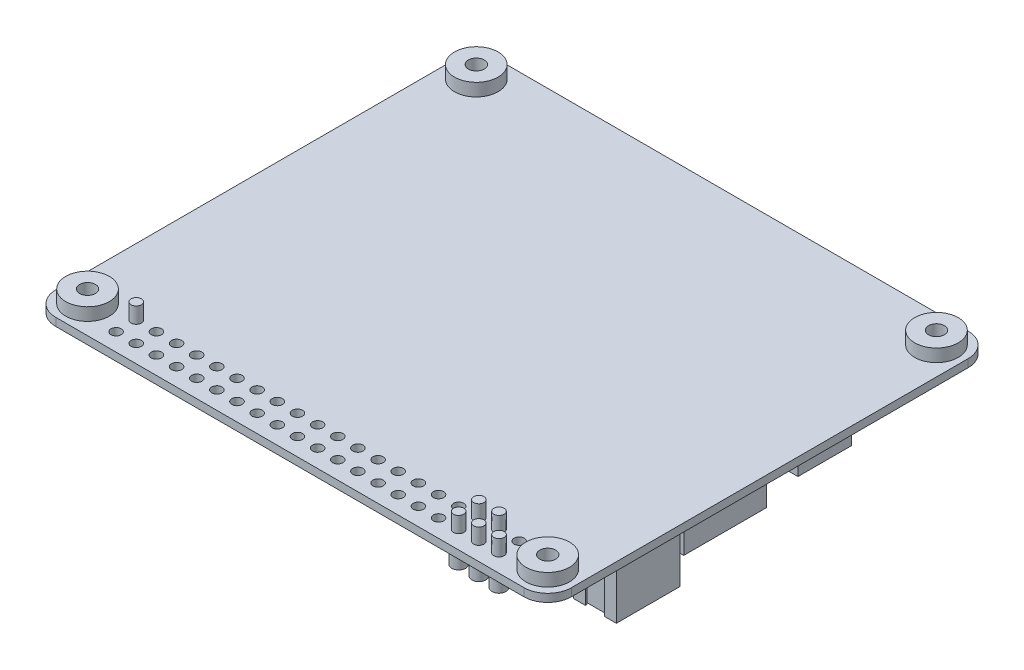
SolidWorks part; units mm, degrees
ref_plane "前视基准面" through (0, 0, 0) normal (0, 0, 1) x (1, 0, 0)
ref_plane "上视基准面" through (0, 0, 0) normal (0, 1, 0) x (1, 0, 0)
ref_plane "右视基准面" through (0, 0, 0) normal (1, 0, 0) x (0, 0, -1)
sketch "草图1" plane through (0, 0, 0) normal (0, 1, 0) x (1, 0, 0)
  line L1 (32.5, -28) -> (-32.5, -28)
  line L2 (32.5, -28) -> (32.5, 28)
  line L3 (32.5, 28) -> (-32.5, 28)
  line L4 (-32.5, -28) -> (-32.5, 28)
  line L5 (32.5, -28) -> (-32.5, 28) construction
  line L6 (32.5, 28) -> (-32.5, -28) construction
  point P0 (0, 0)
  dimension "D1" = 56
  dimension "D2" = 65
extrude "凸台-拉伸1" add sketch "草图1" along normal blind 1
fillet "圆角1" radius 3 4 edges at (32.5, 0.5, -28) (32.5, 0.5, 28) (-32.5, 0.5, 28) (-32.5, 0.5, -28)
sketch "草图2" plane through (0, 1, 0) normal (0, 1, 0) x (1, 0, 0)
  line L0 (-29, -24.5) -> (-29, 24.5) construction
  line L1 (-32.5, 0) -> (-29, 0) construction
  line L2 (-32.5, 25) -> (-32.5, -25) construction
  line L3 (29, 24.5) -> (29, -24.5) construction
  line L4 (29, 0) -> (32.5, 0) construction
  line L5 (32.5, -25) -> (32.5, 25) construction
  circle A0 centre (-29, 24.5) radius 2.75
  circle A1 centre (29, 24.5) radius 2.75
  circle A2 centre (-29, -24.5) radius 2.75
  circle A3 centre (29, -24.5) radius 2.75
  point P16 (28.9437, 21.4052)
  dimension "D1" = 5.5
  dimension "D2" = 49
  dimension "D3" = 58
extrude "凸台-拉伸2" add sketch "草图2" along normal blind 1.6
sketch "草图3" plane through (0, 2.6, 0) normal (0, 1, 0) x (1, 0, 0)
  circle A0 centre (-29, 24.5) radius 1
  circle A1 centre (29, 24.5) radius 1
  circle A2 centre (-29, -24.5) radius 1
  circle A3 centre (29, -24.5) radius 1
  dimension "D1" = 2
extrude "切除-拉伸1" cut sketch "草图3" against normal up to next
sketch "草图4" plane through (0, 0, 0) normal (0, -1, 0) x (1, 0, 0)
  line L0 (29.5, -28) -> (-29.5, -28) construction
  line L1 (25.5, -28) -> (16.5, -28)
  line L2 (25.5, -28) -> (25.5, -20.6)
  line L3 (25.5, -20.6) -> (16.5, -20.6)
  line L4 (16.5, -28) -> (16.5, -20.6)
  line L5 (32.5, 25) -> (32.5, -25) construction
  dimension "D1" = 7.4
  dimension "D2" = 9
  dimension "D3" = 7
extrude "凸台-拉伸3" add sketch "草图4" along normal blind 3.2
sketch "草图5" plane through (0, 0, -28) normal (0, 0, -1) x (-1, 0, 0)
  line L0 (-29.5, 0) -> (-25.5, 0) construction
  line L1 (-16.5, -3.2) -> (-25.5, -3.2)
  line L2 (-16.5, -3.2) -> (-16.5, 0)
  line L3 (-16.5, 0) -> (-25.5, 0)
  line L4 (-25.5, -3.2) -> (-25.5, 0)
  line L5 (-25.5, -3.2) -> (-25.5, 0) construction
extrude "凸台-拉伸4" add sketch "草图5" along normal blind 1
fillet "圆角3" radius 1 4 edges at (25.5, 0, -28.5) (25.5, -3.2, -24.8) (16.5, -3.2, -24.8) (16.5, 0, -28.5)
sketch "草图6" plane through (0, 0, 0) normal (0, -1, 0) x (1, 0, 0)
  line L0 (-32.5, -25) -> (-32.5, 25) construction
  circle A0 centre (-17.5, 0) radius 7
  point P4 (0, 0)
  dimension "D1" = 14
  dimension "D2" = 15
extrude "凸台-拉伸5" add sketch "草图6" along normal blind 2
sketch "草图8" plane through (0, 0, 0) normal (0, -1, 0) x (1, 0, 0)
  circle A0 centre (29, 24.5) radius 2
  circle A1 centre (29, -24.5) radius 2
  circle A2 centre (-29, -24.5) radius 2
  circle A3 centre (-29, 24.5) radius 2
  point P8 (29, -24.5)
  point P10 (29, 24.5)
  point P12 (-29, 24.5)
  point P14 (-29, -24.5)
  dimension "D1" = 4
extrude "凸台-拉伸6" add sketch "草图8" along normal blind 0.5
sketch "草图9" plane through (0, 0, 0) normal (0, 1, 0) x (1, 0, 0)
  circle A0 centre (-29, 24.5) radius 1
  circle A1 centre (29, 24.5) radius 1
  circle A2 centre (-29, -24.5) radius 1
  circle A3 centre (29, -24.5) radius 1
  circle A4 centre (29, -24.5) radius 2 construction
  circle A5 centre (29, 24.5) radius 2 construction
  circle A6 centre (-29, -24.5) radius 2 construction
  circle A7 centre (-29, 24.5) radius 2 construction
  point P16 (-29, -24.5)
  dimension "D1" = 2
extrude "切除-拉伸2" cut sketch "草图9" against normal up to next
sketch "草图10" plane through (0, 0, -29) normal (0, 0, -1) x (-1, 0, 0)
  line L8 (-17.5, -0.2) -> (-24.5, -0.2)
  line L9 (-25.3, -1) -> (-25.3, -2.2)
  line L10 (-24.5, -3) -> (-17.5, -3)
  line L11 (-16.7, -2.2) -> (-16.7, -1)
  line L12 (-17.5, -0.2) -> (-24.5, -0.2)
  line L13 (-25.3, -1) -> (-25.3, -2.2)
  line L14 (-24.5, -3) -> (-17.5, -3)
  line L15 (-16.7, -2.2) -> (-16.7, -1)
  arc A8 (-24.5, -0.2) -> (-25.3, -1) centre (-24.5, -1) ccw
  arc A9 (-25.3, -2.2) -> (-24.5, -3) centre (-24.5, -2.2) ccw
  arc A10 (-17.5, -3) -> (-16.7, -2.2) centre (-17.5, -2.2) ccw
  arc A11 (-16.7, -1) -> (-17.5, -0.2) centre (-17.5, -1) ccw
  arc A12 (-24.5, -0.2) -> (-25.3, -1) centre (-24.5, -1) ccw
  arc A13 (-25.3, -2.2) -> (-24.5, -3) centre (-24.5, -2.2) ccw
  arc A14 (-17.5, -3) -> (-16.7, -2.2) centre (-17.5, -2.2) ccw
  arc A15 (-16.7, -1) -> (-17.5, -0.2) centre (-17.5, -1) ccw
  dimension "D1" = 0.2
extrude "切除-拉伸3" cut sketch "草图10" against normal blind 8
sketch "草图12" plane through (0, 0, 0) normal (0, -1, 0) x (1, 0, 0)
  line L0 (16.5, -28) -> (-29.5, -28) construction
  line L1 (-16.6, -28) -> (-23.9, -28)
  line L2 (-16.6, -28) -> (-16.6, -22.7)
  line L3 (-16.6, -22.7) -> (-23.9, -22.7)
  line L4 (-23.9, -28) -> (-23.9, -22.7)
  line L5 (-32.5, -25) -> (-32.5, 25) construction
  dimension "D1" = 7.3
  dimension "D2" = 8.6
  dimension "D3" = 5.3
extrude "凸台-拉伸8" add sketch "草图12" along normal blind 2.4
sketch "草图13" plane through (0, 0, -28) normal (0, 0, -1) x (-1, 0, 0)
  line L1 (23.9, -2.4) -> (16.6, -2.4)
  line L2 (23.9, -2.4) -> (23.9, 0)
  line L3 (23.9, 0) -> (16.6, 0)
  line L4 (16.6, -2.4) -> (16.6, 0)
extrude "凸台-拉伸9" add sketch "草图13" along normal up to surface (1 mm away) up to face at (21, -1.6, -29)
chamfer "倒角1" distance 0.4 angle 45 2 edges at (-16.6, -2.4, -25.85) (-23.9, -2.4, -25.85)
chamfer "倒角2" distance 1 angle 45 2 edges at (-16.6, 0, -28.5) (-23.9, 0, -28.5)
sketch "草图14" plane through (0, 0, -29) normal (0, 0, -1) x (-1, 0, 0)
  line L16 (22.8172, -0.2) -> (17.6828, -0.2)
  line L17 (17.6828, -0.2) -> (16.8, -1.0828)
  line L18 (16.8, -1.0828) -> (16.8, -1.9172)
  line L19 (16.8, -1.9172) -> (17.0828, -2.2)
  line L20 (17.0828, -2.2) -> (23.4172, -2.2)
  line L21 (23.4172, -2.2) -> (23.7, -1.9172)
  line L22 (23.7, -1.9172) -> (23.7, -1.0828)
  line L23 (23.7, -1.0828) -> (22.8172, -0.2)
  line L24 (22.8172, -0.2) -> (17.6828, -0.2)
  line L25 (17.6828, -0.2) -> (16.8, -1.0828)
  line L26 (16.8, -1.0828) -> (16.8, -1.9172)
  line L27 (16.8, -1.9172) -> (17.0828, -2.2)
  line L28 (17.0828, -2.2) -> (23.4172, -2.2)
  line L29 (23.4172, -2.2) -> (23.7, -1.9172)
  line L30 (23.7, -1.9172) -> (23.7, -1.0828)
  line L31 (23.7, -1.0828) -> (22.8172, -0.2)
  dimension "D1" = 0.2
extrude "切除-拉伸4" cut sketch "草图14" against normal blind 2.4
sketch "草图17" plane through (0, 0, -28) normal (0, 0, -1) x (-1, 0, 0)
  line L0 (23.9, -1) -> (23.9, 0)
  line L1 (23.9, 0) -> (22.9, 0)
  line L2 (22.9, 0) -> (23.9, -1)
  line L3 (16.6, 0) -> (17.6, 0)
  line L4 (17.6, 0) -> (16.6, -1)
  line L5 (16.6, -1) -> (16.6, 0) construction
  line L6 (16.6, -1) -> (16.6, 0)
extrude "切除-拉伸5" cut sketch "草图17" against normal up to surface (5.3 mm away) up to face at (-20.25, -1.4667, -22.7)
fillet "圆角4" radius 0.2 1 edges at (-17.5, -2, -7)
sketch "草图19" plane through (0, 0, 0) normal (0, -1, 0) x (1, 0, 0)
  line L0 (32.5, 25) -> (32.5, -25) construction
  line L1 (32, 18.85) -> (26.6, 18.85)
  line L2 (32, 18.85) -> (32, 10.85)
  line L3 (32, 10.85) -> (26.6, 10.85)
  line L4 (26.6, 18.85) -> (26.6, 10.85)
  line L5 (-29.5, 28) -> (29.5, 28) construction
  dimension "D1" = 8
  dimension "D2" = 5.4
  dimension "D3" = 0.5
  dimension "D4" = 9.15
extrude "凸台-拉伸13" add sketch "草图19" along normal blind 6.22
sketch "草图20" plane through (0, -6.22, 0) normal (0, -1, 0) x (1, 0, 0)
  line L0 (30.5, 18.85) -> (30.5, 18.65)
  line L1 (32, 18.85) -> (26.6, 18.85) construction
  line L2 (30.5, 18.65) -> (31.3599, 18.65)
  line L3 (31.3599, 18.65) -> (31.3599, 18.45)
  line L4 (31.3599, 18.45) -> (26.9378, 18.45)
  line L5 (26.9378, 18.45) -> (26.9378, 18.65)
  line L6 (26.9378, 18.65) -> (28.1, 18.65)
  line L7 (28.1, 18.65) -> (28.1, 18.85)
  line L8 (32, 18.85) -> (26.6, 18.85) construction
  line L9 (28.1, 18.85) -> (30.5, 18.85)
  line L10 (30.5, 10.85) -> (30.5, 11.05)
  line L11 (26.6, 10.85) -> (32, 10.85) construction
  line L12 (30.5, 11.05) -> (31.3599, 11.05)
  line L13 (31.3599, 11.05) -> (31.3599, 11.25)
  line L14 (31.3599, 11.25) -> (26.9378, 11.25)
  line L15 (26.9378, 11.25) -> (26.9378, 11.05)
  line L16 (26.9378, 11.05) -> (28.1, 11.05)
  line L17 (28.1, 11.05) -> (28.1, 10.85)
  line L18 (28.1, 10.85) -> (30.5, 10.85)
  line L19 (32, 10.85) -> (32, 18.85) construction
  line L20 (26.6, 18.85) -> (26.6, 10.85) construction
  dimension "D1" = 0.2
  dimension "D2" = 0.2
  dimension "D3" = 0.2
  dimension "D4" = 1.5
  dimension "D5" = 1.5
  dimension "D6" = 4.4222
  dimension "D7" = 0.6401
extrude "切除-拉伸6" cut sketch "草图20" against normal blind 6.22
sketch "草图21" plane through (0, -6.22, 0) normal (0, -1, 0) x (1, 0, 0)
  line L1 (31.3599, 18.0753) -> (26.9378, 18.0753)
  line L2 (31.3599, 18.0753) -> (31.3599, 11.6247)
  line L3 (31.3599, 11.6247) -> (26.9378, 11.6247)
  line L4 (26.9378, 18.0753) -> (26.9378, 11.6247)
  line L5 (31.3599, 18.0753) -> (26.9378, 11.6247) construction
  line L6 (31.3599, 11.6247) -> (26.9378, 18.0753) construction
  point P0 (29.1489, 14.85)
extrude "切除-拉伸7" cut sketch "草图21" against normal blind 5
sketch "草图22" plane through (0, -1.22, 0) normal (0, -1, 0) x (1, 0, 0)
  line L1 (29.5742, 16.0721) -> (29.0742, 16.0721)
  line L2 (29.5742, 16.0721) -> (29.5742, 15.5721)
  line L3 (29.5742, 15.5721) -> (29.0742, 15.5721)
  line L4 (29.0742, 16.0721) -> (29.0742, 15.5721)
  line L5 (29.5742, 16.0721) -> (29.0742, 15.5721) construction
  line L6 (29.5742, 15.5721) -> (29.0742, 16.0721) construction
  line L7 (29.5566, 14.331) -> (29.0566, 14.331)
  line L8 (29.5566, 14.331) -> (29.5566, 13.831)
  line L9 (29.5566, 13.831) -> (29.0566, 13.831)
  line L10 (29.0566, 14.331) -> (29.0566, 13.831)
  line L11 (29.5566, 14.331) -> (29.0566, 13.831) construction
  line L12 (29.5566, 13.831) -> (29.0566, 14.331) construction
  point P0 (29.3242, 15.8221)
  point P5 (29.3066, 14.081)
  dimension "D1" = 0.5
extrude "凸台-拉伸14" add sketch "草图22" along normal blind 5
chamfer "倒角3" distance 0.1 angle 45 8 edges at (29.3066, -6.22, 14.331) (29.5566, -6.22, 14.081) (29.3066, -6.22, 13.831) (29.0566, -6.22, 14.081) (29.3242, -6.22, 16.0721) (29.5742, -6.22, 15.8221) (29.3242, -6.22, 15.5721) (29.0742, -6.22, 15.8221)
sketch "草图26" plane through (0, 0, 0) normal (0, -1, 0) x (1, 0, 0)
  line L0 (-29.5, 28) -> (29.5, 28) construction
  line L1 (-24.13, 25.77) -> (24.13, 25.77) construction
  line L2 (32.5, 25) -> (32.5, -25) construction
  line L3 (24.13, 23.23) -> (-24.13, 23.23) construction
  circle A0 centre (24.13, 25.77) radius 0.65
  circle A40 centre (21.59, 25.77) radius 0.65
  circle A41 centre (19.05, 25.77) radius 0.65
  circle A42 centre (16.51, 25.77) radius 0.65
  circle A43 centre (13.97, 25.77) radius 0.65
  circle A44 centre (11.43, 25.77) radius 0.65
  circle A45 centre (8.89, 25.77) radius 0.65
  circle A46 centre (6.35, 25.77) radius 0.65
  circle A47 centre (3.81, 25.77) radius 0.65
  circle A48 centre (1.27, 25.77) radius 0.65
  circle A49 centre (-1.27, 25.77) radius 0.65
  circle A50 centre (-3.81, 25.77) radius 0.65
  circle A51 centre (-6.35, 25.77) radius 0.65
  circle A52 centre (-8.89, 25.77) radius 0.65
  circle A53 centre (-11.43, 25.77) radius 0.65
  circle A54 centre (-13.97, 25.77) radius 0.65
  circle A55 centre (-16.51, 25.77) radius 0.65
  circle A56 centre (-19.05, 25.77) radius 0.65
  circle A57 centre (-21.59, 25.77) radius 0.65
  circle A58 centre (-24.13, 25.77) radius 0.65
  circle A59 centre (21.59, 23.23) radius 0.65
  circle A60 centre (19.05, 23.23) radius 0.65
  circle A61 centre (16.51, 23.23) radius 0.65
  circle A62 centre (13.97, 23.23) radius 0.65
  circle A63 centre (11.43, 23.23) radius 0.65
  circle A64 centre (8.89, 23.23) radius 0.65
  circle A65 centre (6.35, 23.23) radius 0.65
  circle A66 centre (3.81, 23.23) radius 0.65
  circle A67 centre (1.27, 23.23) radius 0.65
  circle A68 centre (-1.27, 23.23) radius 0.65
  circle A69 centre (-3.81, 23.23) radius 0.65
  circle A70 centre (-6.35, 23.23) radius 0.65
  circle A71 centre (-8.89, 23.23) radius 0.65
  circle A72 centre (-11.43, 23.23) radius 0.65
  circle A73 centre (-13.97, 23.23) radius 0.65
  circle A74 centre (-16.51, 23.23) radius 0.65
  circle A75 centre (-19.05, 23.23) radius 0.65
  circle A76 centre (-21.59, 23.23) radius 0.65
  circle A77 centre (-24.13, 23.23) radius 0.65
  circle A78 centre (24.13, 23.23) radius 0.65
  point P82 (0, 0)
  dimension "D1" = 1.3
  dimension "D4" = 2.23
  dimension "D5" = 48.26
  dimension "D6" = 8.37
  dimension "D7" = 2.54
  dimension "D2" = 20
  dimension "D3" = 2
extrude "切除-拉伸8" cut sketch "草图26" against normal up to surface (1 mm away) up to face at (29, 1, 27.25)
sketch "草图27" plane through (0, 0, 0) normal (0, -1, 0) x (1, 0, 0)
  circle A0 centre (24.13, 25.77) radius 1.15
  circle A1 centre (21.59, 25.77) radius 1.15
  circle A2 centre (21.59, 23.23) radius 1.15
  circle A3 centre (19.05, 25.77) radius 1.15
  circle A4 centre (19.05, 23.23) radius 1.15
  circle A5 centre (13.97, 23.23) radius 1.15
  circle A6 centre (21.59, 25.77) radius 0.65 construction
  dimension "D1" = 2.3
extrude "凸台-拉伸18" add sketch "草图27" along normal blind 0.8
sketch "草图28" plane through (0, -0.8, 0) normal (0, -1, 0) x (-1, 0, 0)
  circle A0 centre (-24.13, -25.77) radius 0.875
  circle A1 centre (-21.59, -25.77) radius 0.875
  circle A2 centre (-19.05, -23.23) radius 0.875
  circle A3 centre (-21.59, -23.23) radius 0.875
  circle A4 centre (-19.05, -25.77) radius 0.875
  circle A5 centre (-13.97, -23.23) radius 0.875
  dimension "D1" = 1.75
extrude "凸台-拉伸19" add sketch "草图28" along normal blind 2
sketch "草图29" plane through (0, 0, 0) normal (0, 1, 0) x (1, 0, 0)
  circle A0 centre (19.05, -23.23) radius 0.65 construction
  circle A1 centre (19.05, -25.77) radius 0.65 construction
  circle A2 centre (21.59, -23.23) radius 0.65 construction
  circle A4 centre (24.13, -25.77) radius 0.65 construction
  circle A5 centre (-24.13, -23.23) radius 0.65 construction
  circle A6 centre (19.05, -23.23) radius 0.65
  circle A7 centre (19.05, -25.77) radius 0.65
  circle A8 centre (21.59, -23.23) radius 0.65
  circle A9 centre (21.59, -25.77) radius 0.65
  circle A10 centre (24.13, -25.77) radius 0.65
  circle A11 centre (-24.13, -23.23) radius 0.65
  circle A12 centre (21.59, -25.77) radius 0.65 construction
extrude "凸台-拉伸20" add sketch "草图29" along normal blind 3
sketch "草图30" plane through (0, 0, -28) normal (0, 0, -1) x (-1, 0, 0)
  line L0 (-16.5, 0) -> (-17.5, 0)
  line L1 (-16.5, 0) -> (-16.5, -1) construction
  line L2 (-16.5, 0) -> (-16.5, -1)
  line L3 (-25.5, 0) -> (-24.5, 0)
  line L4 (-25.5, -1) -> (-25.5, 0) construction
  line L5 (-25.5, -1) -> (-25.5, 0)
  arc A0 (-16.5, -1) -> (-17.5, 0) centre (-17.5, -1) ccw construction
  arc A1 (-16.5, -1) -> (-17.5, 0) centre (-17.5, -1) ccw
  arc A2 (-24.5, 0) -> (-25.5, -1) centre (-24.5, -1) ccw construction
  arc A3 (-24.5, 0) -> (-25.5, -1) centre (-24.5, -1) ccw
extrude "切除-拉伸9" cut sketch "草图30" against normal up to next
sketch "草图31" plane through (0, 0, 0) normal (0, -1, 0) x (1, 0, 0)
  line L0 (-269.1222, 141.019) -> (182.8778, 141.019) construction
  line L1 (24.5, -20.6) -> (17.5, -20.6) construction
  line L2 (31.459, 9.8102) -> (19.8345, 9.8102)
  line L3 (31.459, 9.8102) -> (31.459, -0.6109)
  line L4 (31.459, -0.6109) -> (19.8345, -0.6109)
  line L5 (19.8345, 9.8102) -> (19.8345, -0.6109)
  line L6 (31.459, -1.1785) -> (28.1669, -1.1785)
  line L7 (31.459, -1.1785) -> (31.459, -4.516)
  line L8 (31.459, -4.516) -> (28.1669, -4.516)
  line L9 (28.1669, -1.1785) -> (28.1669, -4.516)
  line L10 (27.1452, -1.4056) -> (22.332, -1.4056)
  line L11 (27.1452, -1.4056) -> (27.1452, -4.1981)
  line L12 (27.1452, -4.1981) -> (22.332, -4.1981)
  line L13 (22.332, -1.4056) -> (22.332, -4.1981)
  line L14 (31.0503, -4.9928) -> (23.558, -4.9928)
  line L15 (31.0503, -4.9928) -> (31.0503, -11.7586)
  line L16 (31.0503, -11.7586) -> (23.558, -11.7586)
  line L17 (23.558, -4.9928) -> (23.558, -11.7586)
  line L18 (31.459, -13.2884) -> (30.0812, -13.2884)
  line L19 (31.459, -13.2884) -> (31.459, -15.1195)
  line L20 (31.459, -15.1195) -> (30.0812, -15.1195)
  line L21 (30.0812, -13.2884) -> (30.0812, -15.1195)
  line L22 (29.3946, -12.2203) -> (27.6398, -12.2203)
  line L23 (29.3946, -12.2203) -> (29.3946, -13.0596)
  line L24 (29.3946, -13.0596) -> (27.6398, -13.0596)
  line L25 (27.6398, -12.2203) -> (27.6398, -13.0596)
  line L26 (25.1221, -19.2775) -> (23.024, -19.2775)
  line L27 (25.1221, -19.2775) -> (25.1221, -20.6)
  line L28 (25.1221, -20.6) -> (23.024, -20.6)
  line L29 (23.024, -19.2775) -> (23.024, -20.6)
  line L30 (24.5, -20.6) -> (17.5, -20.6) construction
  line L31 (21.8033, -19.2775) -> (20.7352, -19.2775)
  line L32 (21.8033, -19.2775) -> (21.8033, -20.6)
  line L33 (21.8033, -20.6) -> (20.7352, -20.6)
  line L34 (20.7352, -19.2775) -> (20.7352, -20.6)
  line L35 (-4.9095, -24.5987) -> (-6.2095, -24.5987)
  line L36 (20.2393, -19.2775) -> (19.2474, -19.2775)
  line L37 (20.2393, -19.2775) -> (20.2393, -20.6)
  line L38 (20.2393, -20.6) -> (19.2474, -20.6)
  line L39 (19.2474, -19.2775) -> (19.2474, -20.6)
  line L40 (25.1221, -17.065) -> (23.024, -17.065)
  line L41 (25.1221, -17.065) -> (25.1221, -18.5146)
  line L42 (25.1221, -18.5146) -> (23.024, -18.5146)
  line L43 (23.024, -17.065) -> (23.024, -18.5146)
  line L44 (21.2692, -13.0596) -> (18.103, -13.0596)
  line L45 (21.2692, -13.0596) -> (21.2692, -16.3402)
  line L46 (21.2692, -16.3402) -> (18.103, -16.3402)
  line L47 (18.103, -13.0596) -> (18.103, -16.3402)
  line L48 (19.2474, -0.6109) -> (18.4047, -0.6109)
  line L49 (19.2474, -0.6109) -> (19.2474, -2.216)
  line L50 (19.2474, -2.216) -> (18.4047, -2.216)
  line L51 (18.4047, -0.6109) -> (18.4047, -2.216)
  line L52 (13.1588, -24.973) -> (8.3931, -24.973)
  line L53 (13.1588, -24.973) -> (13.1588, -27.3005)
  line L54 (13.1588, -27.3005) -> (8.3931, -27.3005)
  line L55 (8.3931, -24.973) -> (8.3931, -27.3005)
  line L56 (4.6988, -24.973) -> (0, -24.973)
  line L57 (4.6988, -24.973) -> (4.6988, -27.3005)
  line L58 (4.6988, -27.3005) -> (0, -27.3005)
  line L59 (0, -24.973) -> (0, -27.3005)
  line L60 (8.3931, 15.9758) -> (4.9221, 15.9758)
  line L61 (8.3931, 15.9758) -> (8.3931, 13.2491)
  line L62 (8.3931, 13.2491) -> (4.9221, 13.2491)
  line L63 (4.9221, 15.9758) -> (4.9221, 13.2491)
  line L64 (8.3931, 11.7221) -> (4.9221, 11.7221)
  line L65 (8.3931, 11.7221) -> (8.3931, 9.0318)
  line L66 (8.3931, 9.0318) -> (4.9221, 9.0318)
  line L67 (4.9221, 11.7221) -> (4.9221, 9.0318)
  line L68 (9.6847, 6.3051) -> (5.9037, 6.3051)
  line L69 (9.6847, 6.3051) -> (9.6847, 1.4698)
  line L70 (9.6847, 1.4698) -> (5.9037, 1.4698)
  line L71 (5.9037, 6.3051) -> (5.9037, 1.4698)
  line L80 (-1.5572, -24.1659) -> (-3.3676, -24.1659)
  line L81 (-1.5572, -24.1659) -> (-1.5572, -27.3005)
  line L82 (-1.5572, -27.3005) -> (-3.3676, -27.3005)
  line L83 (-3.3676, -24.1659) -> (-3.3676, -27.3005)
  line L88 (-4.9095, -24.5987) -> (-4.9095, -26.7453)
  line L89 (-4.9095, -26.7453) -> (-6.2095, -26.7453)
  line L90 (-6.2095, -24.5987) -> (-6.2095, -26.7453)
  line L92 (-7.0018, -24.5987) -> (-8.3018, -24.5987)
  line L93 (-7.0018, -24.5987) -> (-7.0018, -26.7453)
  line L94 (-7.0018, -26.7453) -> (-8.3018, -26.7453)
  line L95 (-8.3018, -24.5987) -> (-8.3018, -26.7453)
  line L96 (-9.1473, -24.5987) -> (-10.4473, -24.5987)
  line L97 (-9.1473, -24.5987) -> (-9.1473, -26.7453)
  line L98 (-9.1473, -26.7453) -> (-10.4473, -26.7453)
  line L99 (-10.4473, -24.5987) -> (-10.4473, -26.7453)
  line L100 (-11.2125, -24.5987) -> (-12.5125, -24.5987)
  line L101 (-11.2125, -24.5987) -> (-11.2125, -26.7453)
  line L102 (-11.2125, -26.7453) -> (-12.5125, -26.7453)
  line L103 (-12.5125, -24.5987) -> (-12.5125, -26.7453)
  line L104 (-13.2578, -24.5987) -> (-14.5578, -24.5987)
  line L105 (-13.2578, -24.5987) -> (-13.2578, -26.7453)
  line L106 (-13.2578, -26.7453) -> (-14.5578, -26.7453)
  line L107 (-14.5578, -24.5987) -> (-14.5578, -26.7453)
  line L108 (0.6545, -17.8156) -> (-0.8398, -17.8156)
  line L109 (0.6545, -17.8156) -> (0.6545, -19.6835)
  line L110 (0.6545, -19.6835) -> (-0.8398, -19.6835)
  line L111 (-0.8398, -17.8156) -> (-0.8398, -19.6835)
  line L112 (-9.9754, -18.0873) -> (-11.6734, -18.0873)
  line L113 (-9.9754, -18.0873) -> (-9.9754, -18.9703)
  line L114 (-9.9754, -18.9703) -> (-11.6734, -18.9703)
  line L115 (-11.6734, -18.0873) -> (-11.6734, -18.9703)
  line L116 (-1.2233, 3.594) -> (-2.668, 3.594)
  line L117 (-1.2233, 3.594) -> (-1.2233, 1.8282)
  line L118 (-1.2233, 1.8282) -> (-2.668, 1.8282)
  line L119 (-2.668, 3.594) -> (-2.668, 1.8282)
  line L120 (-2.2552, -2.7581) -> (-3.1725, -2.7581)
  line L121 (-2.2552, -2.7581) -> (-2.2552, -4.516)
  line L122 (-2.2552, -4.516) -> (-3.1725, -4.516)
  line L123 (-3.1725, -2.7581) -> (-3.1725, -4.516)
  line L124 (-4.6401, -2.7581) -> (-5.5344, -2.7581)
  line L125 (-4.6401, -2.7581) -> (-4.6401, -4.516)
  line L126 (-4.6401, -4.516) -> (-5.5344, -4.516)
  line L127 (-5.5344, -2.7581) -> (-5.5344, -4.516)
  line L128 (-6.2095, -3.8955) -> (-7.2269, -3.8955)
  line L129 (-6.2095, -3.8955) -> (-6.2095, -5.7277)
  line L130 (-6.2095, -5.7277) -> (-7.2269, -5.7277)
  line L131 (-7.2269, -3.8955) -> (-7.2269, -5.7277)
  line L132 (-7.6341, -3.8955) -> (-8.5039, -3.8955)
  line L133 (-7.6341, -3.8955) -> (-7.6341, -5.7277)
  line L134 (-7.6341, -5.7277) -> (-8.5039, -5.7277)
  line L135 (-8.5039, -3.8955) -> (-8.5039, -5.7277)
  line L136 (-8.8925, -3.8955) -> (-9.8179, -3.8955)
  line L137 (-8.8925, -3.8955) -> (-8.8925, -5.7277)
  line L138 (-8.8925, -5.7277) -> (-9.8179, -5.7277)
  line L139 (-9.8179, -3.8955) -> (-9.8179, -5.7277)
  line L140 (-10.188, -3.8955) -> (-11.2125, -3.8955)
  line L141 (-10.188, -3.8955) -> (-10.188, -5.7277)
  line L142 (-10.188, -5.7277) -> (-11.2125, -5.7277)
  line L143 (-11.2125, -3.8955) -> (-11.2125, -5.7277)
  line L144 (12.5814, 9.3712) -> (10.7759, 9.3712)
  line L145 (12.5814, 9.3712) -> (12.5814, 8.2563)
  line L146 (12.5814, 8.2563) -> (10.7759, 8.2563)
  line L147 (10.7759, 9.3712) -> (10.7759, 8.2563)
  line L148 (11.6787, 7.8846) -> (10.0309, 7.8846)
  line L149 (11.6787, 7.8846) -> (11.6787, 6.9555)
  line L150 (11.6787, 6.9555) -> (10.0309, 6.9555)
  line L151 (10.0309, 7.8846) -> (10.0309, 6.9555)
  line L152 (12.1492, 6.3051) -> (10.4025, 6.3051)
  line L153 (12.1492, 6.3051) -> (12.1492, 5.2831)
  line L154 (12.1492, 5.2831) -> (10.4025, 5.2831)
  line L155 (10.4025, 6.3051) -> (10.4025, 5.2831)
  line L156 (12.1492, 1.4698) -> (10.4025, 1.4698)
  line L157 (12.1492, 1.4698) -> (12.1492, 0.5632)
  line L158 (12.1492, 0.5632) -> (10.4025, 0.5632)
  line L159 (10.4025, 1.4698) -> (10.4025, 0.5632)
  line L160 (11.6787, -0.3659) -> (10.4025, -0.3659)
  line L161 (11.6787, -0.3659) -> (11.6787, -2.216)
  line L162 (11.6787, -2.216) -> (10.4025, -2.216)
  line L163 (10.4025, -0.3659) -> (10.4025, -2.216)
  line L164 (10.0309, -0.3659) -> (8.9159, -0.3659)
  line L165 (10.0309, -0.3659) -> (10.0309, -2.216)
  line L166 (10.0309, -2.216) -> (8.9159, -2.216)
  line L167 (8.9159, -0.3659) -> (8.9159, -2.216)
  line L168 (8.9159, 7.8846) -> (7.2064, 7.8846)
  line L169 (8.9159, 7.8846) -> (8.9159, 6.9555)
  line L170 (8.9159, 6.9555) -> (7.2064, 6.9555)
  line L171 (7.2064, 7.8846) -> (7.2064, 6.9555)
  line L172 (6.5746, 0.5632) -> (5.6083, 0.5632)
  line L173 (6.5746, 0.5632) -> (6.5746, -0.9234)
  line L174 (6.5746, -0.9234) -> (5.6083, -0.9234)
  line L175 (5.6083, 0.5632) -> (5.6083, -0.9234)
  line L176 (4.9221, 1.8282) -> (3.1926, 1.8282)
  line L177 (4.9221, 1.8282) -> (4.9221, 1.0165)
  line L178 (4.9221, 1.0165) -> (3.1926, 1.0165)
  line L179 (3.1926, 1.8282) -> (3.1926, 1.0165)
  line L180 (4.9221, 0.2287) -> (4.0574, 0.2287)
  line L181 (4.9221, 0.2287) -> (4.9221, -1.4056)
  line L182 (4.9221, -1.4056) -> (4.0574, -1.4056)
  line L183 (4.0574, 0.2287) -> (4.0574, -1.4056)
  line L184 (3.6386, 0.2287) -> (2.7466, 0.2287)
  line L185 (3.6386, 0.2287) -> (3.6386, -1.4056)
  line L186 (3.6386, -1.4056) -> (2.7466, -1.4056)
  line L187 (2.7466, 0.2287) -> (2.7466, -1.4056)
  line L188 (5.3755, 3.0635) -> (4.4942, 3.0635)
  line L189 (5.3755, 3.0635) -> (5.3755, 4.8142)
  line L190 (1.6317, 2.3471) -> (3.1926, 2.3471)
  line L191 (1.6317, 2.3471) -> (1.6317, 3.3134)
  line L192 (1.6317, 3.3134) -> (3.1926, 3.3134)
  line L193 (3.1926, 2.3471) -> (3.1926, 3.3134)
  line L194 (5.3755, 4.8142) -> (4.4942, 4.8142)
  line L195 (4.4942, 3.0635) -> (4.4942, 4.8142)
  line L196 (-26.4365, 18.1309) -> (-28.123, 18.1309)
  line L197 (-26.4365, 18.1309) -> (-26.4365, 14.8151)
  line L198 (-26.4365, 14.8151) -> (-28.123, 14.8151)
  line L199 (-28.123, 18.1309) -> (-28.123, 14.8151)
  line L200 (-14.8746, -12.2203) -> (-16.6449, -12.2203)
  line L201 (-14.8746, -12.2203) -> (-14.8746, -13.1933)
  line L202 (-14.8746, -13.1933) -> (-16.6449, -13.1933)
  line L203 (-16.6449, -12.2203) -> (-16.6449, -13.1933)
  line L204 (-14.2012, -14.6161) -> (-17.3617, -14.6161)
  line L205 (-14.2012, -14.6161) -> (-14.2012, -16.5384)
  line L206 (-14.2012, -16.5384) -> (-17.3617, -16.5384)
  line L207 (-17.3617, -14.6161) -> (-17.3617, -16.5384)
  line L208 (-17.8504, -16.6905) -> (-18.8061, -16.6905)
  line L209 (-17.8504, -16.6905) -> (-17.8504, -18.363)
  line L210 (-17.8504, -18.363) -> (-18.8061, -18.363)
  line L211 (-18.8061, -16.6905) -> (-18.8061, -18.363)
  line L212 (-19.4653, -16.6905) -> (-20.411, -16.6905)
  line L213 (-19.4653, -16.6905) -> (-19.4653, -18.363)
  line L214 (-19.4653, -18.363) -> (-20.411, -18.363)
  line L215 (-20.411, -16.6905) -> (-20.411, -18.363)
  line L216 (-21.0003, -16.6905) -> (-21.9533, -16.6905)
  line L217 (-21.0003, -16.6905) -> (-21.0003, -18.363)
  line L218 (-21.0003, -18.363) -> (-21.9533, -18.363)
  line L219 (-21.9533, -16.6905) -> (-21.9533, -18.363)
  line L220 (-22.4419, -16.6905) -> (-23.3932, -16.6905)
  line L221 (-22.4419, -16.6905) -> (-22.4419, -18.363)
  line L222 (-22.4419, -18.363) -> (-23.3932, -18.363)
  line L223 (-23.3932, -16.6905) -> (-23.3932, -18.363)
  line L224 (-19.5638, -11.4061) -> (-22.1884, -11.4061)
  line L225 (-19.5638, -11.4061) -> (-19.5638, -14.9023)
  line L226 (-19.5638, -14.9023) -> (-22.1884, -14.9023)
  line L227 (-22.1884, -11.4061) -> (-22.1884, -14.9023)
  dimension "D1" = 1.3
extrude "凸台-拉伸21" add sketch "草图31" along normal blind 0.6
sketch "草图32" plane through (0, -0.6, 0) normal (0, -1, 0) x (1, 0, 0)
  line L4 (31.459, -0.6109) -> (31.459, 9.8102)
  line L5 (31.459, 9.8102) -> (19.8345, 9.8102)
  line L6 (19.8345, 9.8102) -> (19.8345, -0.6109)
  line L7 (19.8345, -0.6109) -> (31.459, -0.6109)
  line L8 (31.459, -0.6109) -> (31.459, 9.8102)
  line L9 (31.459, 9.8102) -> (19.8345, 9.8102)
  line L10 (19.8345, 9.8102) -> (19.8345, -0.6109)
  line L11 (19.8345, -0.6109) -> (31.459, -0.6109)
  dimension "D1" = 0
extrude "凸台-拉伸22" add sketch "草图32" along normal blind 3
sketch "草图33" plane through (0, -0.6, 0) normal (0, -1, 0) x (1, 0, 0)
  line L4 (31.0503, -11.7586) -> (31.0503, -4.9928)
  line L5 (31.0503, -4.9928) -> (23.558, -4.9928)
  line L6 (23.558, -4.9928) -> (23.558, -11.7586)
  line L7 (23.558, -11.7586) -> (31.0503, -11.7586)
  line L8 (31.0503, -11.7586) -> (31.0503, -4.9928)
  line L9 (31.0503, -4.9928) -> (23.558, -4.9928)
  line L10 (23.558, -4.9928) -> (23.558, -11.7586)
  line L11 (23.558, -11.7586) -> (31.0503, -11.7586)
  dimension "D1" = 0
extrude "凸台-拉伸23" add sketch "草图33" along normal blind 2
sketch "草图34" plane through (0, -0.6, 0) normal (0, -1, 0) x (1, 0, 0)
  line L0 (13.1588, -27.3005) -> (13.1588, -24.973) construction
  line L1 (13.1588, -24.973) -> (8.3931, -24.973) construction
  line L2 (8.3931, -24.973) -> (8.3931, -27.3005) construction
  line L3 (8.3931, -27.3005) -> (13.1588, -27.3005) construction
  line L4 (4.6988, -27.3005) -> (4.6988, -24.973) construction
  line L5 (4.6988, -24.973) -> (0, -24.973) construction
  line L6 (0, -24.973) -> (0, -27.3005) construction
  line L7 (0, -27.3005) -> (4.6988, -27.3005) construction
  line L8 (13.1588, -27.3005) -> (13.1588, -24.973)
  line L9 (13.1588, -24.973) -> (8.3931, -24.973)
  line L10 (8.3931, -24.973) -> (8.3931, -27.3005)
  line L11 (8.3931, -27.3005) -> (13.1588, -27.3005)
  line L12 (4.6988, -27.3005) -> (4.6988, -24.973)
  line L13 (4.6988, -24.973) -> (0, -24.973)
  line L14 (0, -24.973) -> (0, -27.3005)
  line L15 (0, -27.3005) -> (4.6988, -27.3005)
extrude "凸台-拉伸24" add sketch "草图34" along normal blind 1
sketch "草图35" plane through (0, 0, -27.3005) normal (0, 0, -1) x (-1, 0, 0)
  line L0 (-2.3494, 0) -> (-2.3494, -1.6) construction
  line L1 (0, 0) -> (-4.6988, 0) construction
  line L4 (-8.3931, -1.6) -> (-13.1588, -1.6) construction
  line L5 (-1.1494, -1.3) -> (-3.5494, -1.3)
  line L6 (-1.1494, -1.3) -> (-1.1494, -0.3)
  line L7 (-1.1494, -0.3) -> (-3.5494, -0.3)
  line L8 (-3.5494, -1.3) -> (-3.5494, -0.3)
  line L9 (-1.1494, -1.3) -> (-3.5494, -0.3) construction
  line L10 (-1.1494, -0.3) -> (-3.5494, -1.3) construction
  line L11 (-9.5759, -1.3) -> (-11.9759, -1.3)
  line L12 (-9.5759, -1.3) -> (-9.5759, -0.3)
  line L13 (-9.5759, -0.3) -> (-11.9759, -0.3)
  line L14 (-11.9759, -1.3) -> (-11.9759, -0.3)
  line L15 (-9.5759, -1.3) -> (-11.9759, -0.3) construction
  line L16 (-9.5759, -0.3) -> (-11.9759, -1.3) construction
  line L17 (0, -1.6) -> (-4.6988, -1.6) construction
  point P0 (-10.7759, -0.8)
  point P2 (-2.3494, -0.8)
  point P10 (-2.3494, 0)
  point P13 (-10.7759, -1.6)
  point P17 (-2.3494, -1.6)
  point P19 (-2.3494, -0.8)
  dimension "D1" = 2.4
  dimension "D2" = 1
extrude "凸台-拉伸25" add sketch "草图35" along normal blind 0.8
